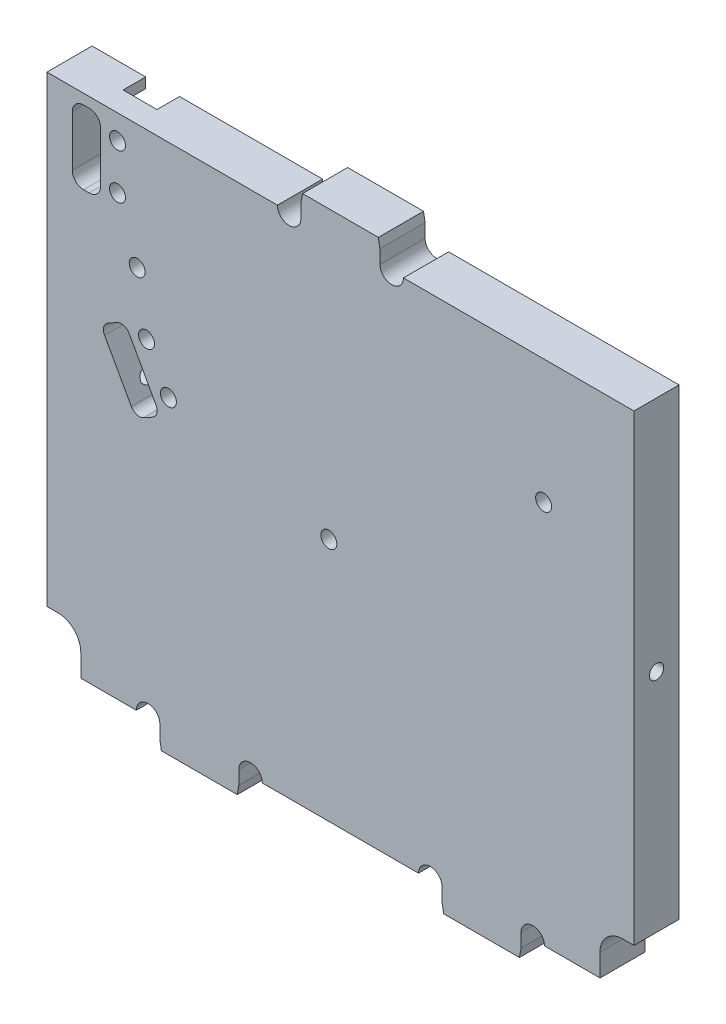
SolidWorks part; units mm, degrees
material "PE High Density"
ref_plane "Front Plane" through (0, 0, 0) normal (0, 0, 1) x (1, 0, 0)
ref_plane "Top Plane" through (0, 0, 0) normal (0, 1, 0) x (1, 0, 0)
ref_plane "Right Plane" through (0, 0, 0) normal (1, 0, 0) x (0, 0, -1)
sketch "Sketch1" plane through (0, 0, 0) normal (0, 0, 1) x (1, 0, 0)
  line L1 (-82.55, -71.4375) -> (82.55, -71.4375)
  line L2 (-82.55, -71.4375) -> (-82.55, 71.4375)
  line L3 (-82.55, 71.4375) -> (82.55, 71.4375)
  line L4 (82.55, -71.4375) -> (82.55, 71.4375)
  line L5 (-82.55, -71.4375) -> (82.55, 71.4375) construction
  line L6 (-82.55, 71.4375) -> (82.55, -71.4375) construction
  point P0 (0, 0)
  dimension "D1" = 165.1
  dimension "D2" = 142.875
extrude "Boss-Extrude1" add sketch "Sketch1" along normal blind 12.7
sketch "Sketch2" plane through (0, 0, 12.7) normal (0, 0, 1) x (1, 0, 0)
  line L0 (82.55, 71.4375) -> (-82.55, 71.4375) construction
  line L1 (-11.1125, 71.4375) -> (11.1125, 71.4375)
  line L2 (-11.1125, 71.4375) -> (-11.1125, 75.2475)
  line L3 (-10.6646, 77.7875) -> (10.6646, 77.7875)
  line L4 (11.1125, 71.4375) -> (11.1125, 75.2475)
  line L5 (10.6646, 77.7875) -> (11.1125, 75.2475)
  line L6 (-10.6646, 77.7875) -> (-11.1125, 75.2475)
  line L7 (82.55, -71.4375) -> (82.55, 71.4375) construction
  point P6 (0, 77.7875)
  dimension "D3" = 170
  dimension "D4" = 170
  dimension "D5" = 3.81
  dimension "D1" = 71.4375
  dimension "D2" = 6.35
extrude "Boss-Extrude2" add sketch "Sketch2" against normal up to surface (12.7 mm away) up to face at (0, 0, 0)
sketch "Sketch4" plane through (0, 0, 12.7) normal (0, 0, 1) x (1, 0, 0)
  line L0 (-11.1125, 71.4375) -> (-82.55, 71.4375) construction
  line L1 (-11.1125, 75.2475) -> (-11.1125, 71.4375) construction
  line L2 (-82.55, 71.4375) -> (82.55, 71.4375) construction
  line L3 (0, 77.7875) -> (0, 0) construction
  line L4 (10.6646, 77.7875) -> (-10.6646, 77.7875) construction
  line L5 (-17.7165, 71.4375) -> (-11.1125, 71.4375)
  line L6 (11.1125, 71.4375) -> (17.7165, 71.4375)
  arc A0 (-17.7165, 71.4375) -> (-11.1125, 71.4375) centre (-14.4145, 71.4375) ccw
  arc A1 (17.7165, 71.4375) -> (11.1125, 71.4375) centre (14.4145, 71.4375) cw
  dimension "D1" = 6.604
  dimension "D2" = 3.302
extrude "Cut-Extrude1" cut sketch "Sketch4" against normal up to next contours A1 L6 | A0 L5
sketch "Sketch5" plane through (0, 0, 12.7) normal (0, 0, 1) x (1, 0, 0)
  line L0 (-82.55, -71.4375) -> (82.55, -71.4375) construction
  line L1 (50.8, -71.4375) -> (28.575, -71.4375)
  line L2 (50.8, -71.4375) -> (50.8, -75.2475)
  line L3 (50.3521, -77.7875) -> (29.0229, -77.7875)
  line L4 (28.575, -71.4375) -> (28.575, -75.2475)
  line L6 (28.575, -75.2475) -> (29.0229, -77.7875)
  line L7 (50.8, -75.2475) -> (50.3521, -77.7875)
  dimension "D1" = 22.225
  dimension "D2" = 6.35
  dimension "D3" = 28.575
  dimension "D4" = 170
  dimension "D5" = 170
  dimension "D6" = 3.81
extrude "Boss-Extrude3" add sketch "Sketch5" against normal up to surface (12.7 mm away) up to face at (0, 48.768, 0)
sketch "Sketch6" plane through (0, 0, 12.7) normal (0, 0, 1) x (1, 0, 0)
  line L0 (-82.55, -71.4375) -> (28.575, -71.4375) construction
  line L1 (82.55, -71.4375) -> (0, -71.4375) construction
  line L2 (21.971, -71.4375) -> (28.575, -71.4375)
  line L3 (39.6875, -77.7875) -> (39.6875, 71.4375) construction
  line L4 (29.0229, -77.7875) -> (50.3521, -77.7875) construction
  line L5 (82.55, 71.4375) -> (17.7165, 71.4375) construction
  line L6 (50.8, -71.4375) -> (57.404, -71.4375)
  arc A0 (28.575, -71.4375) -> (21.971, -71.4375) centre (25.273, -71.4375) ccw
  arc A1 (50.8, -71.4375) -> (57.404, -71.4375) centre (54.102, -71.4375) cw
  dimension "D1" = 6.604
  dimension "D2" = 3.302
extrude "Cut-Extrude2" cut sketch "Sketch6" against normal up to surface (12.7 mm away) up to face at (13.2292, 7.5706, 0)
mirror "Mirror1" about plane through (0, 0, 0) normal (1, 0, 0) of "Boss-Extrude3", "Cut-Extrude2"
hole_wizard "#21 (0.159) Diameter Hole1" positions "Sketch25" profile "Sketch26" hole size "#21" standard "ANSI Inch"
sketch "Sketch25" plane through (82.55, 0, 0) normal (1, 0, 0) x (0, 0, -1)
  line L0 (-12.7, -71.4375) -> (0, -71.4375) construction
  point P0 (-6.35, 4.7625)
  point P6 (-6.35, -71.4375)
  dimension "D1" = 76.2
sketch "Sketch26" plane through (82.55, 4.7625, 6.35) normal (0, 1, 0) x (0, 0, -1)
  line L0 (0, 0) -> (0, 23.4383)
  line L1 (0, 23.4383) -> (2.0193, 22.225)
  line L2 (2.0193, 22.225) -> (2.0193, 0)
  line L5 (2.0193, 0) -> (0, 0)
  line L10 (0, 23.4383) -> (-2.0193, 22.225) construction
  line L11 (0, -6.35) -> (0, 107.95) construction
  dimension "Hole Dia." = 4.0386
  dimension "Hole Depth" = 22.225
  dimension "Drill Angle" = 118
hole_wizard "#21 (0.159) Diameter Hole2" positions "Sketch27" profile "Sketch28" hole size "#21" standard "ANSI Inch"
sketch "Sketch27" plane through (-82.55, 0, 0) normal (-1, 0, 0) x (0, 0, 1)
  point P0 (6.35, 4.7625)
sketch "Sketch28" plane through (-82.55, 4.7625, 6.35) normal (0, 1, 0) x (0, 0, 1)
  line L0 (0, 0) -> (0, 23.4383)
  line L1 (0, 23.4383) -> (2.0193, 22.225)
  line L2 (2.0193, 22.225) -> (2.0193, 0)
  line L5 (2.0193, 0) -> (0, 0)
  line L10 (0, 23.4383) -> (-2.0193, 22.225) construction
  line L11 (0, -6.35) -> (0, 107.95) construction
  dimension "Hole Dia." = 4.0386
  dimension "Hole Depth" = 22.225
  dimension "Drill Angle" = 118
sketch "Sketch21" plane through (0, 0, 0) normal (0, 0, -1) x (-1, 0, 0)
  line L1 (-82.55, -71.4375) -> (-82.55, 71.4375) construction
  line L2 (82.55, 71.4375) -> (82.55, -71.4375) construction
  line L4 (82.55, -71.4375) -> (57.404, -71.4375) construction
  circle A0 centre (-57.15, 36.5125) radius 4.7625
  circle A1 centre (57.15, 36.5125) radius 4.7625
  circle A2 centre (-57.15, 36.5125) radius 114.3 construction
  circle A4 centre (3.263, -2.7527) radius 3.175
  circle A5 centre (3.263, -2.7527) radius 55.5625 construction
  circle A6 centre (57.15, 36.5125) radius 66.675 construction
  point P13 (38.1, -46.0375)
  dimension "D1" = 9.525
  dimension "D3" = 228.6
  dimension "D6" = 6.35
  dimension "D7" = 111.125
  dimension "D5" = 133.35
  dimension "D4" = 25.4
  dimension "D8" = 44.45
  dimension "D9" = 25.4
  dimension "D2" = 107.95
extrude "Cut-Extrude10" cut sketch "Sketch21" against normal blind 6.35
hole_wizard "#8 Clearance Hole1" positions "Sketch22" profile "Sketch23" hole size "#8" standard "ANSI Inch"
sketch "Sketch22" plane through (0, 0, 0) normal (0, 0, -1) x (-1, 0, 0)
  point P0 (-57.15, 36.5125)
  point P3 (3.263, -2.7527)
  point P6 (57.15, 36.5125)
sketch "Sketch23" plane through (57.15, 36.5125, 0) normal (1, 0, 0) x (0, 1, 0)
  line L0 (0, 0) -> (0, 20.4007)
  line L1 (0, 20.4007) -> (2.2479, 19.05)
  line L2 (2.2479, 19.05) -> (2.2479, 0)
  line L5 (2.2479, 0) -> (0, 0)
  line L10 (0, 20.4007) -> (-2.2479, 19.05) construction
  line L11 (0, -6.35) -> (0, 107.95) construction
  dimension "Hole Dia." = 4.4958
  dimension "Hole Depth" = 19.05
  dimension "Drill Angle" = 118
sketch "Sketch24" plane through (0, 0, 12.7) normal (0, 0, 1) x (1, 0, 0)
  line L1 (-82.55, -71.4375) -> (-73.025, -71.4375)
  line L2 (-82.55, -71.4375) -> (-82.55, -58.7375)
  line L3 (-82.55, -58.7375) -> (-73.025, -58.7375)
  line L4 (-73.025, -71.4375) -> (-73.025, -58.7375)
  line L5 (82.55, -71.4375) -> (73.025, -71.4375)
  line L6 (82.55, -71.4375) -> (82.55, -58.7375)
  line L7 (82.55, -58.7375) -> (73.025, -58.7375)
  line L8 (73.025, -71.4375) -> (73.025, -58.7375)
  dimension "D1" = 9.525
  dimension "D2" = 12.7
extrude "Cut-Extrude11" cut sketch "Sketch24" against normal through all
fillet "Fillet1" radius 6.35 2 edges at (73.025, -58.7375, 6.35) (-73.025, -58.7375, 6.35)
sketch "Sketch29" plane through (0, 0, 0) normal (0, 0, -1) x (-1, 0, 0)
  line L0 (17.7165, 71.4375) -> (82.55, 71.4375) construction
  line L5 (57.9438, 45.0875) -> (67.4688, 45.0875)
  line L6 (57.9438, 45.0875) -> (57.9437, 71.4375)
  line L7 (57.9437, 71.4375) -> (67.4688, 71.4375)
  line L8 (67.4688, 45.0875) -> (67.4688, 71.4375)
  line L9 (82.55, 71.4375) -> (82.55, -58.7375) construction
  point P4 (67.4688, 58.2625)
  dimension "D2" = 13.175
  dimension "D3" = 9.525
  dimension "D4" = 15.0812
extrude "Cut-Extrude12" cut sketch "Sketch29" against normal blind 6.35
fillet "Fillet2" radius 3.175 2 edges at (-67.4688, 45.0875, 3.175) (-57.9438, 45.0875, 3.175)
hole_wizard "#8 Clearance Hole2" positions "Sketch30" profile "Sketch31" hole size "#8" standard "ANSI Inch" end condition through all
sketch "Sketch30" plane through (0, 0, 6.35) normal (0, 0, -1) x (-1, 0, 0)
  line L0 (67.4688, 71.4375) -> (57.9437, 71.4375) construction
  line L1 (62.7062, 64.6125) -> (62.7062, 51.9125) construction
  line L3 (67.4688, 71.4375) -> (82.55, 71.4375) construction
  point P0 (62.7062, 64.6125)
  point P2 (62.7062, 51.9125)
  point P8 (62.7062, 71.4375)
  point P13 (62.7063, 58.2625)
  dimension "D2" = 13.175
  dimension "D1" = 12.7
sketch "Sketch31" plane through (-62.7062, 64.6125, 6.35) normal (1, 0, 0) x (0, 1, 0)
  line L0 (0, 0) -> (0, 6.35)
  line L1 (0, 6.35) -> (2.2479, 6.35)
  line L2 (2.2479, 6.35) -> (2.2479, 0)
  line L5 (2.2479, 0) -> (0, 0)
  line L11 (0, -6.35) -> (0, 107.95) construction
  dimension "Thru Hole Dia." = 4.4958
  dimension "Thru Hole Depth" = 6.35
sketch "Sketch32" plane through (0, 0, 0) normal (0, 0, -1) x (-1, 0, 0)
  line L0 (67.4688, 48.2625) -> (67.4688, 71.4375) construction
  line L1 (67.4688, 68.5812) -> (75.4062, 68.5812)
  line L2 (67.4688, 68.5812) -> (67.4688, 47.9437)
  line L3 (67.4688, 47.9437) -> (75.4062, 47.9437)
  line L4 (75.4062, 68.5812) -> (75.4062, 47.9437)
  line L5 (62.7062, 64.6125) -> (62.7062, 51.9125) construction
  point P10 (67.4688, 58.2625)
  point P11 (62.7062, 58.2625)
  dimension "D1" = 20.6375
  dimension "D2" = 7.9375
extrude "Cut-Extrude13" cut sketch "Sketch32" against normal through all
sketch "Sketch33" plane through (0, 0, 0) normal (0, 0, -1) x (-1, 0, 0)
  line L0 (67.4688, 47.9437) -> (67.4527, 47.9437)
  line L1 (67.4688, 48.2625) -> (67.4688, 47.9437)
  arc A0 (64.2938, 45.0875) -> (67.4688, 48.2625) centre (64.2938, 48.2625) ccw construction
  arc A1 (67.4527, 47.9437) -> (67.4688, 48.2625) centre (64.2938, 48.2625) ccw
extrude "Cut-Extrude14" cut sketch "Sketch33" against normal up to surface (6.35 mm away) up to face at (-64.9541, 64.6125, 6.35)
fillet "Fillet3" radius 3.175 4 edges at (-75.4062, 47.9437, 6.35) (-67.4688, 47.9437, 9.525) (-67.4688, 68.5812, 9.525) (-75.4062, 68.5812, 6.35)
sketch "Sketch34" plane through (0, 0, 0) normal (0, 0, -1) x (-1, 0, 0)
  line L0 (40.7577, 5.3028) -> (53.8415, 28.9066)
  line L1 (53.8415, 28.9066) -> (62.1723, 24.2888)
  line L2 (62.1723, 24.2888) -> (49.0885, 0.685)
  line L3 (49.0885, 0.685) -> (40.7577, 5.3028)
  line L4 (67.4688, 71.4375) -> (67.4688, 12.3742) construction
  line L5 (62.7062, 64.6125) -> (62.7062, 51.9125) construction
  line L6 (55.6304, 12.4869) -> (47.2996, 17.1047) construction
  circle A0 centre (57.15, 36.5125) radius 2.2479 construction
  point P13 (62.7062, 58.2625)
  dimension "D1" = 26.9875
  dimension "D2" = 151
  dimension "D3" = 10.3187
  dimension "D4" = 10.3187
  dimension "D5" = 21.75
  dimension "D6" = 9.525
  dimension "D7" = 21.75
extrude "Cut-Extrude15" cut sketch "Sketch34" against normal blind 6.35
hole_wizard "#8 Clearance Hole3" positions "Sketch35" profile "Sketch36" hole size "#8" standard "ANSI Inch" end condition through all
sketch "Sketch35" plane through (0, 0, 6.35) normal (0, 0, -1) x (-1, 0, 0)
  line L0 (58.0069, 26.5977) -> (44.9231, 2.9939) construction
  line L1 (62.1723, 24.2888) -> (53.8415, 28.9066) construction
  line L2 (40.7577, 5.3028) -> (49.0885, 0.685) construction
  point P0 (54.5435, 20.3496)
  point P2 (48.3865, 9.242)
  point P11 (0, 0)
  point P12 (55.7887, 22.5959)
  point P13 (48.4476, 9.3522)
  point P14 (0, 0)
  point P15 (0, 0)
  point P16 (51.465, 14.7958)
  dimension "D1" = 12.7
  dimension "D2" = 6.35
sketch "Sketch36" plane through (-54.5435, 20.3496, 6.35) normal (1, 0, 0) x (0, 1, 0)
  line L0 (0, 0) -> (0, 6.35)
  line L1 (0, 6.35) -> (2.2479, 6.35)
  line L2 (2.2479, 6.35) -> (2.2479, 0)
  line L5 (2.2479, 0) -> (0, 0)
  line L11 (0, -6.35) -> (0, 107.95) construction
  dimension "Thru Hole Dia." = 4.4958
  dimension "Thru Hole Depth" = 6.35
sketch "Sketch37" plane through (0, 0, 0) normal (0, 0, -1) x (-1, 0, 0)
  line L1 (60.633, 21.5119) -> (67.5753, 17.6637)
  line L2 (49.0885, 0.685) -> (62.1723, 24.2888) construction
  line L3 (67.5753, 17.6637) -> (57.57, -0.3863)
  line L4 (57.57, -0.3863) -> (50.6277, 3.4619)
  line L5 (49.0885, 0.685) -> (62.1723, 24.2888) construction
  line L6 (50.6277, 3.4619) -> (60.633, 21.5119)
  point P0 (55.6304, 12.4869)
  point P9 (55.6304, 12.4869)
  point P10 (67.5753, 17.6637)
  point P11 (0, 0)
  dimension "D1" = 7.9375
  dimension "D2" = 20.6375
extrude "Cut-Extrude16" cut sketch "Sketch37" against normal through all
fillet "Fillet4" radius 2.54 8 edges at (-50.6277, 3.4619, 9.525) (-60.633, 21.5119, 9.525) (-67.5753, 17.6637, 6.35) (-57.57, -0.3863, 6.35) (-49.0885, 0.685, 3.175) (-40.7577, 5.3028, 3.175) (-53.8415, 28.9066, 3.175) (-62.1723, 24.2888, 3.175)
equation "\"D4@Sketch2\"=\"D3@Sketch2\""
equation "\"D2@Sketch4\"=\"D1@Sketch4\"/2"
equation "\"D2@Sketch6\"=\"D1@Sketch6\"/2"
equation "\"D4@Sketch21\"=(6.5-(\"D3@Sketch21\"/2))/2"
equation "\"D7@Sketch21\"=4+.375"
equation "\"D5@Sketch21\"=4.5+.75"
equation "\"D2@Sketch1\"=6.000in-.375"
equation "\"D2@Sketch29\"=.125+10mm"
equation "\"D2@Sketch30\"=\"D2@Sketch29\""
equation "\"D4@Sketch29\"=.500+.0625+.03125"
equation "\"D4@Sketch34\"=\"D3@Sketch34\""
equation "\"D7@Sketch34\"=\"D5@Sketch34\""
equation "\"D2@Sketch35\"=\"D1@Sketch35\"/2"
